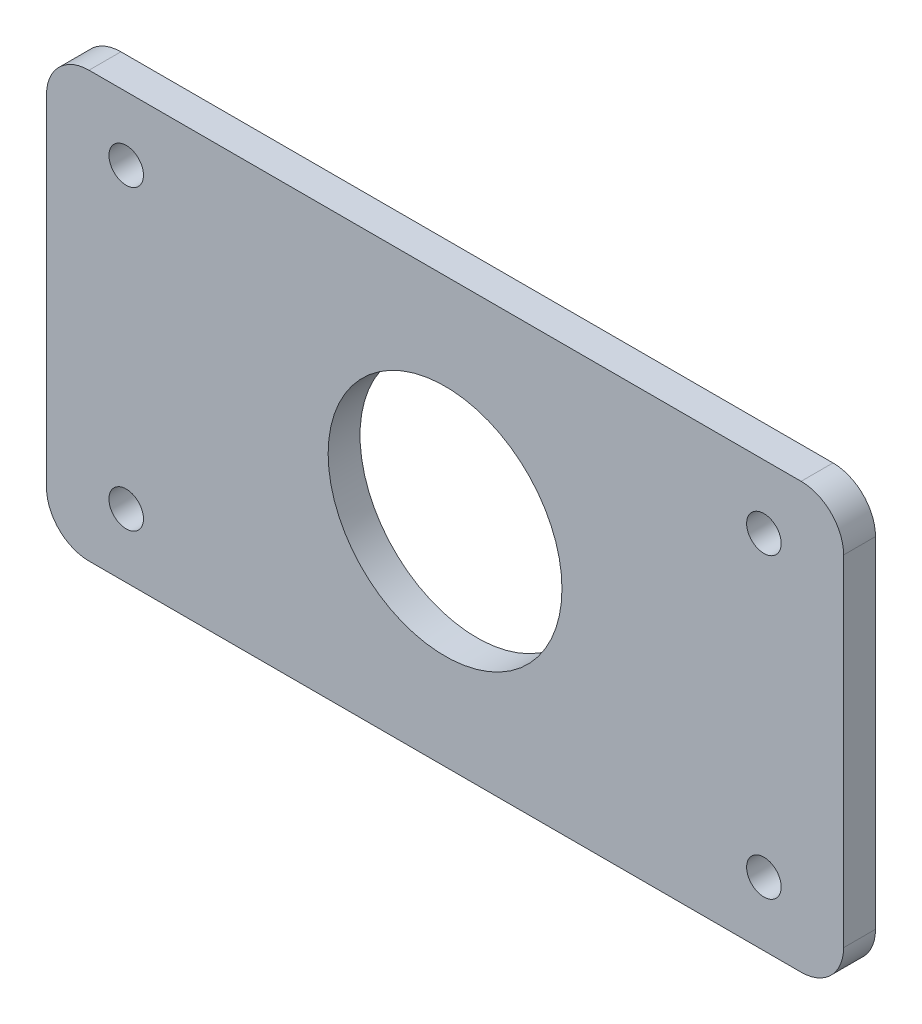
SolidWorks part; units mm, degrees
material "6063-T6"
ref_plane "Front Plane" through (0, 0, 0) normal (0, 0, 1) x (1, 0, 0)
ref_plane "Top Plane" through (0, 0, 0) normal (0, 1, 0) x (1, 0, 0)
ref_plane "Right Plane" through (0, 0, 0) normal (1, 0, 0) x (0, 0, -1)
sketch "Sketch2" plane through (0, 0, 0) normal (0, 0, 1) x (1, 0, 0)
  line L1 (-75, -40) -> (75, -40)
  line L2 (-75, -40) -> (-75, 40)
  line L3 (-75, 40) -> (75, 40)
  line L4 (75, -40) -> (75, 40)
  line L5 (-75, -40) -> (75, 40) construction
  line L6 (-75, 40) -> (75, -40) construction
  point P0 (0, 0)
  dimension "D1" = 150
  dimension "D2" = 80
extrude "Boss-Extrude1" add sketch "Sketch2" along normal mid plane 6
sketch "Sketch3" plane through (0, 0, 3) normal (0, 0, 1) x (1, 0, 0)
  line L4 (75, -40) -> (75, 40)
  line L5 (75, 40) -> (-75, 40)
  line L6 (-75, 40) -> (-75, -40)
  line L7 (-75, -40) -> (75, -40)
  line L8 (75, -40) -> (75, 40)
  line L9 (75, 40) -> (-75, 40)
  line L10 (-75, 40) -> (-75, -40)
  line L11 (-75, -40) -> (75, -40)
  circle A0 centre (-60, 28) radius 3.25
  circle A1 centre (-60, -28) radius 3.25
  circle A2 centre (60, -28) radius 3.25
  circle A3 centre (60, 28) radius 3.25
  circle A4 centre (0, 0) radius 22
  dimension "D2" = 44
  dimension "D3" = 6.5
  dimension "D4" = 15
  dimension "D5" = 12
  dimension "D6" = 12
  dimension "D7" = 15
  dimension "D8" = 15
  dimension "D9" = 12
  dimension "D10" = 15
  dimension "D11" = 12
  dimension "D1" = 0
extrude "Cut-Extrude1" cut sketch "Sketch3" against normal through all both and the other way through all contours A4 | A0 | A1 | A2 | A3
fillet "Fillet2" radius 8 4 edges at (75, 40, 0) (75, -40, 0) (-75, -40, 0) (-75, 40, 0)
